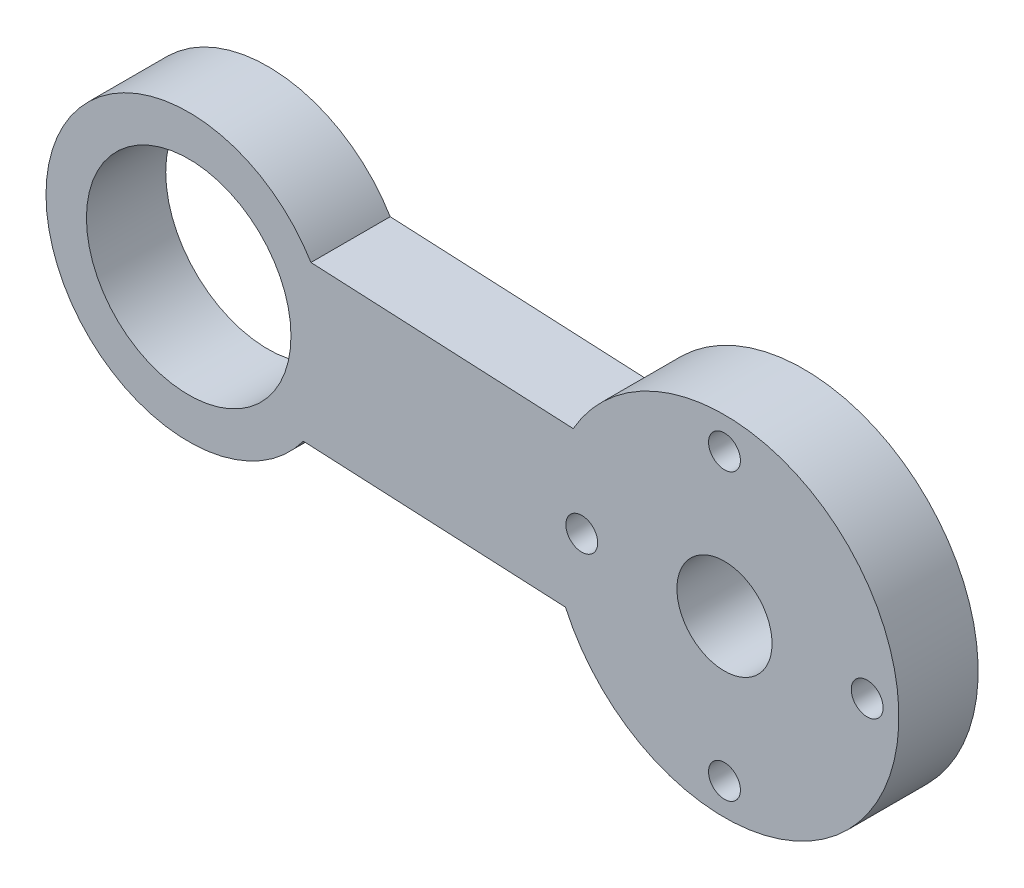
SolidWorks part; units mm, degrees
ref_plane "Plan de face" through (0, 0, 0) normal (0, 0, 1) x (1, 0, 0)
ref_plane "Plan de dessus" through (0, 0, 0) normal (0, 1, 0) x (1, 0, 0)
ref_plane "Plan de droite" through (0, 0, 0) normal (1, 0, 0) x (0, 0, -1)
sketch "Esquisse1" plane through (0, 0, 0) normal (0, 0, 1) x (1, 0, 0)
  line L1 (-10.0259, -4.5257) -> (-40.0259, -3.0709)
  line L2 (-9.541, 5.4743) -> (-39.541, 6.9291)
  line L3 (-40.0259, -3.0709) -> (-39.541, 6.9291)
  arc A0 (-10.0259, -4.5257) -> (-9.541, 5.4743) centre (0, 0) ccw
  dimension "D1" = 22
  dimension "D2" = 10
  dimension "D3" = 30
extrude "Boss.-Extru.1" add sketch "Esquisse1" along normal blind 5
sketch "Esquisse2" plane through (0, 0, 5) normal (0, 0, 1) x (1, 0, 0)
  line L2 (-40.0259, -3.0709) -> (-10.0259, -4.5257) construction
  circle A0 centre (0, 9) radius 1.005
  circle A1 centre (9, 0) radius 1.005
  circle A2 centre (0, -9) radius 1.005
  circle A3 centre (-9, 0) radius 1.005
  circle A4 centre (-33.7908, 1.6326) radius 1.005
  circle A6 centre (0, 0) radius 3
  dimension "D1" = 2.01
  dimension "D2" = 2.01
  dimension "D3" = 2.01
  dimension "D4" = 2.01
  dimension "D5" = 24.7908
  dimension "D6" = 2.01
  dimension "D7" = 6
  dimension "D8" = 9
  dimension "D9" = 9
  dimension "D10" = 9
  dimension "D11" = 9
  dimension "D12" = 5
extrude "Enlèv. mat.-Extru.1" cut sketch "Esquisse2" against normal blind 6
sketch "Esquisse3" plane through (0, 0, 0) normal (0, 0, -1) x (-1, 0, 0)
  circle A0 centre (33.7908, 1.6326) radius 9
  dimension "D1" = 18
extrude "Boss.-Extru.2" add sketch "Esquisse3" against normal blind 5
sketch "Esquisse5" plane through (0, 0, 0) normal (0, 0, -1) x (-1, 0, 0)
  circle A0 centre (33.7908, 1.6326) radius 6.45
  dimension "D1" = 12.9
extrude "Enlèv. mat.-Extru.2" cut sketch "Esquisse5" against normal blind 6
